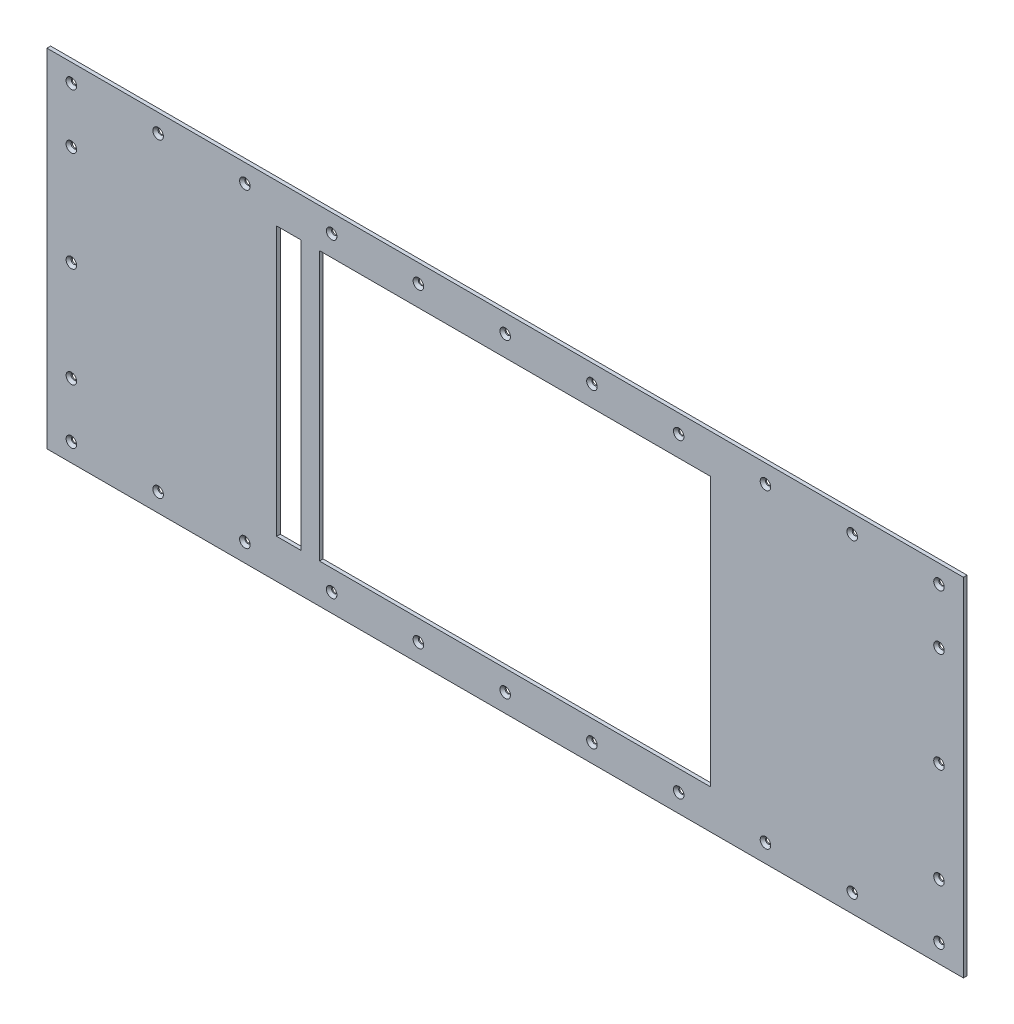
SolidWorks part; units mm, degrees
material "AISI 316 Нержавеющая сталь, лист (SS)"
ref_plane "Спереди" through (0, 0, 0) normal (0, 0, 1) x (1, 0, 0)
ref_plane "Сверху" through (0, 0, 0) normal (0, 1, 0) x (1, 0, 0)
ref_plane "Справа" through (0, 0, 0) normal (1, 0, 0) x (0, 0, -1)
sketch "Эскиз1" plane through (0, 0, 0) normal (0, 0, 1) x (1, 0, 0)
  line L1 (0, 0) -> (750, 0)
  line L2 (0, 0) -> (0, 284)
  line L3 (0, 284) -> (750, 284)
  line L4 (750, 0) -> (750, 284)
  line L5 (223, 32) -> (543, 32)
  line L6 (223, 32) -> (223, 252)
  line L7 (223, 252) -> (543, 252)
  line L8 (543, 32) -> (543, 252)
  line L9 (188, 32) -> (208, 32)
  line L10 (188, 32) -> (188, 252)
  line L11 (188, 252) -> (208, 252)
  line L12 (208, 32) -> (208, 252)
  dimension "D1" = 284
  dimension "D2" = 750
  dimension "D3" = 32
  dimension "D4" = 223
  dimension "D5" = 220
  dimension "D6" = 320
  dimension "D7" = 15
  dimension "D8" = 20
extrude "Бобышка-Вытянуть1" add sketch "Эскиз1" along normal blind 3
hole_wizard "Зенковка для винта с полупотайной головкой M41" positions "Эскиз3" profile "Эскиз2" countersink size "M4" standard "ГОСТ" end condition through all
sketch "Эскиз3" plane through (0, 0, 3) normal (0, 0, 1) x (1, 0, 0)
  line L0 (0, 0) -> (750, 0) construction
  line L1 (750, 284) -> (0, 284) construction
  line L2 (0, 284) -> (0, 0) construction
  point P0 (20, 15)
  point P5 (20, 269)
  point P28 (91, 15)
  point P29 (91, 269)
  point P30 (162, 15)
  point P31 (162, 269)
  point P32 (233, 15)
  point P33 (233, 269)
  point P34 (304, 15)
  point P35 (304, 269)
  point P36 (375, 15)
  point P37 (375, 269)
  point P38 (446, 15)
  point P39 (446, 269)
  point P40 (517, 15)
  point P41 (517, 269)
  point P42 (588, 15)
  point P43 (588, 269)
  point P44 (659, 15)
  point P45 (659, 269)
  point P46 (730, 15)
  point P47 (730, 269)
  dimension "D1" = 15
  dimension "D2" = 15
  dimension "D3" = 20
  dimension "D4" = 11
sketch "Эскиз2" plane through (20, 15, 3) normal (1, 0, 0) x (0, -1, 0)
  line L0 (0, 0) -> (0, 3)
  line L1 (0, 3) -> (2.15, 3)
  line L2 (2.15, 3) -> (2.15, 2.15)
  line L3 (2.15, 2.15) -> (4.3, 0)
  line L5 (4.3, 0) -> (0, 0)
  line L6 (-2.15, 2.15) -> (-4.3, 0) construction
  line L11 (0, -6.35) -> (0, 107.95) construction
  dimension "Диаметр сквозного отверстия" = 4.3
  dimension "Глубина сквозного отверстия" = 3
  dimension "Диаметр передней зенковки" = 8.6
  dimension "Угол передней зенковки" = 90
hole_wizard "Зенковка для винта с полупотайной головкой M42" positions "Эскиз5" profile "Эскиз4" countersink size "M4" standard "ГОСТ" end condition through all
sketch "Эскиз5" plane through (0, 0, 3) normal (0, 0, 1) x (1, 0, 0)
  line L0 (0, 284) -> (0, 0) construction
  line L1 (750, 0) -> (750, 284) construction
  line L2 (750, 284) -> (0, 284) construction
  point P0 (20, 224)
  point P2 (730, 224)
  point P18 (20, 142)
  point P19 (730, 142)
  point P20 (20, 60)
  point P21 (730, 60)
  dimension "D1" = 20
  dimension "D2" = 20
  dimension "D3" = 60
  dimension "D4" = 3
sketch "Эскиз4" plane through (20, 224, 3) normal (1, 0, 0) x (0, -1, 0)
  line L0 (0, 0) -> (0, 3)
  line L1 (0, 3) -> (2.25, 3)
  line L2 (2.25, 3) -> (2.25, 2.05)
  line L3 (2.25, 2.05) -> (4.3, 0)
  line L5 (4.3, 0) -> (0, 0)
  line L6 (-2.25, 2.05) -> (-4.3, 0) construction
  line L11 (0, -6.35) -> (0, 107.95) construction
  dimension "Диаметр сквозного отверстия" = 4.5
  dimension "Глубина сквозного отверстия" = 3
  dimension "Диаметр передней зенковки" = 8.6
  dimension "Угол передней зенковки" = 90
equation "\"D2@Эскиз3\"=\"D1@Эскиз3\""
equation "\"D2@Эскиз5\"=\"D1@Эскиз5\""
